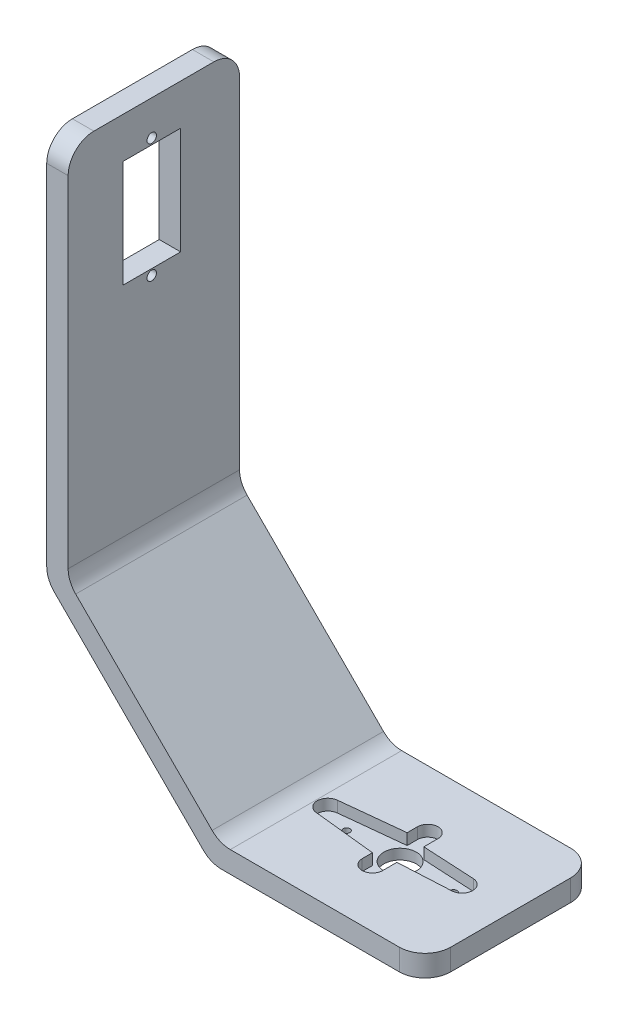
SolidWorks part; units mm, degrees
ref_plane "前视基准面" through (0, 0, 0) normal (0, 0, 1) x (1, 0, 0)
ref_plane "上视基准面" through (0, 0, 0) normal (0, 1, 0) x (1, 0, 0)
ref_plane "右视基准面" through (0, 0, 0) normal (1, 0, 0) x (0, 0, -1)
sketch "草图1" plane through (0, 0, 0) normal (0, 0, 1) x (1, 0, 0)
  line L0 (15.873, -72.2743) -> (-32.056, -72.2743)
  line L3 (-72.4113, -38.9901) -> (-34.127, -77.2743)
  line L4 (-34.127, -77.2743) -> (15.873, -77.2743)
  line L5 (15.873, -77.2743) -> (15.873, -72.2743)
  line L7 (-67.4113, -36.919) -> (-32.056, -72.2743)
  line L8 (-67.4113, -36.919) -> (-67.4113, 51.0099)
  line L9 (-67.4113, 51.0099) -> (-72.4113, 51.0099)
  line L10 (-72.4113, 51.0099) -> (-72.4113, -38.9901)
  dimension "D1" = 135
  dimension "D2" = 50
  dimension "D3" = 5
  dimension "D4" = 5
  dimension "D5" = 5
  dimension "D6" = 90
extrude "凸台-拉伸1" add sketch "草图1" along normal blind 40
fillet "圆角7" radius 6 1 edges at (-34.127, -77.2743, 20)
sketch "草图6" plane through (0, -72.2743, 0) normal (0, 1, 0) x (1, 0, 0)
  line L3 (4.6358, -17.5035) -> (-7.5461, -16.8597)
  line L10 (-7.5461, -13.55) -> (-7.5461, -16.8597)
  line L11 (-12.3461, -13.55) -> (-12.3461, -15.9503)
  line L12 (-27.0603, -17.514) -> (-12.3461, -15.9503)
  line L13 (-27.0603, -22.486) -> (-12.3461, -24.0497)
  line L14 (-12.3461, -24.0497) -> (-12.3461, -26.45)
  line L15 (-7.5461, -23.1403) -> (-7.5461, -26.45)
  line L16 (4.6358, -22.4965) -> (-7.5461, -23.1403)
  arc A13 (-7.5461, -13.55) -> (-12.3461, -13.55) centre (-9.9461, -13.55) ccw
  arc A14 (-27.0603, -17.514) -> (-27.0603, -22.486) centre (-26.7961, -20) ccw
  arc A15 (-7.5461, -26.45) -> (-12.3461, -26.45) centre (-9.9461, -26.45) cw
  arc A17 (4.6358, -22.4965) -> (4.6358, -17.5035) centre (4.5039, -20) ccw
  point P18 (-9.9461, -20)
  point P29 (-8.0461, -20)
  point P30 (-11.8461, -20)
extrude "切除-拉伸4" cut sketch "草图6" against normal blind 2.6
sketch "草图7" plane through (-67.4113, -6.3608, 0) normal (-1, 0, 0) x (0, 0, -1)
  line L0 (-20.5, 4.2731) -> (-20.5, -76.3714) construction
  line L2 (-27.25, -22.839) -> (-27.25, -47.839)
  line L3 (-27.25, -47.839) -> (-13.75, -47.839)
  line L4 (-27.25, -22.839) -> (-13.75, -22.839)
  line L5 (-13.75, -22.839) -> (-13.75, -47.839)
  line L6 (-27.25, -35.339) -> (11.7138, -35.339) construction
  circle A0 centre (-20.5, -49.239) radius 1.1
  circle A1 centre (-20.5, -21.439) radius 1.1
  point P13 (-20.5, -22.839)
  point P14 (-20.5, -47.839)
  dimension "D1" = 13.5
  dimension "D3" = 27.8
  dimension "D2" = 25
  dimension "D4" = 13.9
extrude "切除-拉伸5" cut sketch "草图7" along normal blind 10
fillet "圆角8" radius 6 1 edges at (-32.056, -72.2743, 20)
fillet "圆角9" radius 6 1 edges at (-72.4113, -38.9901, 20)
fillet "圆角10" radius 6 1 edges at (-67.4113, -36.919, 20)
fillet "圆角11" radius 6 1 edges at (-69.9113, 51.0099, 0)
fillet "圆角12" radius 6 1 edges at (-69.9113, 51.0099, 40)
fillet "圆角13" radius 6 1 edges at (15.873, -74.7743, 0)
fillet "圆角14" radius 6 1 edges at (15.873, -74.7743, 40)
ref_plane "基准面1" through (0, 0, 20) normal (0, 0, 1) x (1, 0, 0)
sketch "草图10" plane through (0, -74.8743, 0) normal (0, 1, 0) x (1, 0, 0)
  line L0 (-9.9461, -26.45) -> (-9.9461, -13.55) construction
  line L1 (2.5539, -20) -> (-9.9461, -20) construction
  circle A0 centre (-9.9461, -20) radius 3.8
  circle A1 centre (2.5539, -20) radius 0.8
  circle A2 centre (-22.4461, -20) radius 0.8
  dimension "D1" = 25
  dimension "D2" = 1.6
  dimension "D3" = 7.6
extrude "切除-拉伸7" cut sketch "草图10" against normal blind 10
